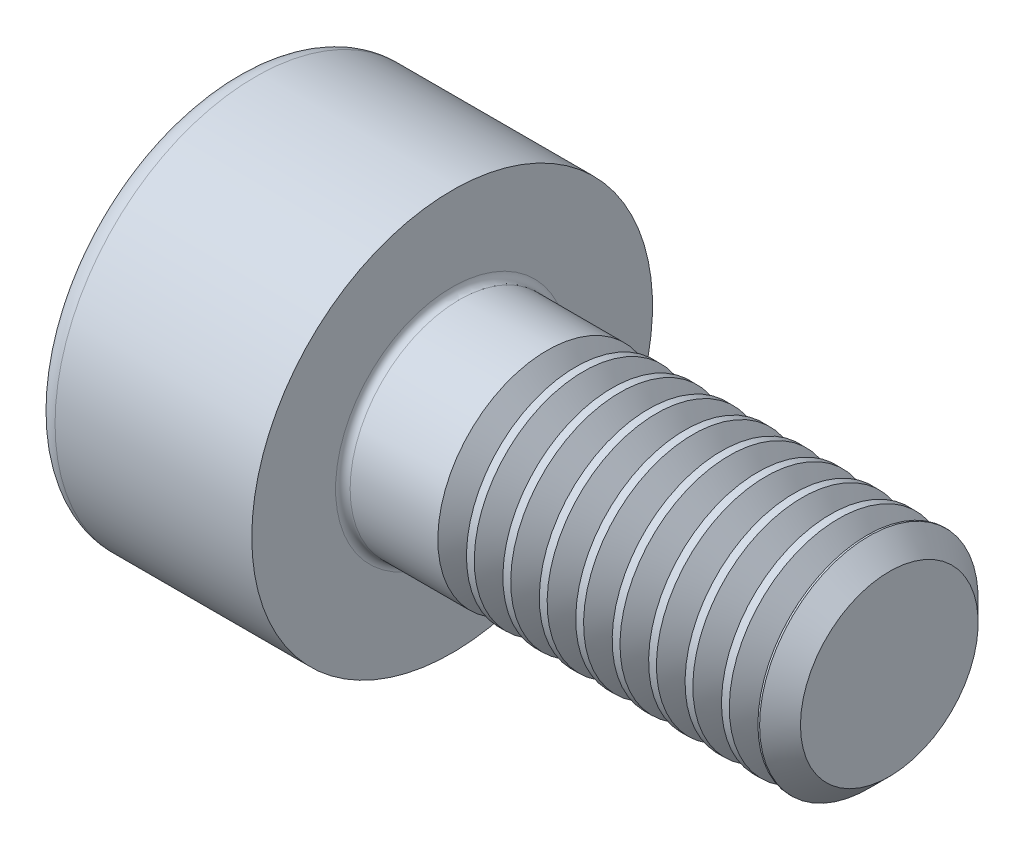
SolidWorks part; units mm, degrees
ref_plane "Plane1" through (0, 0, 0) normal (0, 0, 1) x (1, 0, 0)
ref_plane "Plane2" through (0, 0, 0) normal (0, 1, 0) x (1, 0, 0)
ref_plane "Plane3" through (0, 0, 0) normal (1, 0, 0) x (0, 0, -1)
sketch "BodySke" plane through (0, 0, 0) normal (0, 0, 1) x (1, 0, 0)
  line L0 (0, 0) -> (0, 2.75)
  line L1 (0, 2.75) -> (3, 2.75)
  line L2 (3, 2.75) -> (3, 1.5)
  line L3 (3, 1.5) -> (8.7195, 1.5)
  line L4 (9, 1.2195) -> (9, 0)
  line L5 (9, 0) -> (0, 0)
  line L6 (-31.75, 0) -> (127, 0) construction
  line L8 (9, 1.2195) -> (8.7195, 1.5)
  line L10 (9, -1.2195) -> (8.7195, -1.5) construction
  line L11 (3.5, 9.525) -> (3.5, 3.175) construction
  line L12 (3, 9.525) -> (3, 3.175) construction
  line L13 (-51, 9.525) -> (-51, 3.175) construction
  dimension "Diameter" = 3
  dimension "Head_ht" = 3
  dimension "Length" = 6
  dimension "Body_ch_ang" = 45
  dimension "Head_dia" = 5.5
  dimension "Minor_dia" = 2.439
  dimension "Advance" = 0.5
  dimension "Thread_nom" = 6
  dimension "Thread_length" = 60
revolve "Base-Revolve" add sketch "BodySke"
cosmetic thread "ThreadCosmetic" [suppressed]
fillet "Fillet1" radius 0.1 1 edges at (3, 0, 1.5)
fillet "Fillet2" radius 0.3 1 edges at (0, 0, 2.75)
sketch "Sketch2" plane through (0, 0, 0) normal (0, 0, 1) x (1, 0, 0)
  line L0 (0, 1.26) -> (1.3, 1.26)
  line L1 (1.3, 1.26) -> (2.0275, 0)
  line L2 (-31.75, 0) -> (127, 0) construction
  line L3 (2.0275, 0) -> (0, 0)
  line L4 (0, 0) -> (0, 1.26)
  line L6 (0, 0) -> (47.625, 0) construction
  dimension "D1" = 1.26
  dimension "D2" = 60
  dimension "Depth" = 1.3
revolve "Hex-PreBroach" cut sketch "Sketch2" angle 360 about L6
sketch "Sketch3" plane through (0, 0, 0) normal (-1, 0, 0) x (0, 0.5, 0.866)
  line L0 (0.7275, 1.26) -> (-0.7275, 1.26)
  line L1 (-0.7275, 1.26) -> (-1.4549, 0)
  line L2 (0.7275, 1.26) -> (1.4549, 0)
  line L3 (0.7275, -1.26) -> (1.4549, 0)
  line L4 (0.7275, -1.26) -> (-0.7275, -1.26)
  line L5 (-0.7275, -1.26) -> (-1.4549, 0)
  dimension "D1" = 1.26
  dimension "D2" = 1.26
  dimension "Hex_size" = 2.52
extrude "Hex" cut sketch "Sketch3" against normal blind 1.3
sketch "ThdSchSke" plane through (0, 0, 0) normal (0, 0, 1) x (1, 0, 0)
  line L0 (4.5, -1.2195) -> (4.3036, -1.5)
  line L1 (4.5, -1.2195) -> (4.6964, -1.5)
  line L2 (4.6964, -1.5) -> (4.6964, -1.875)
  line L3 (-3.175, 0) -> (5.1513, 0) construction
  line L4 (0, 2.45) -> (0, -2.45) construction
  line L5 (4.6964, -1.875) -> (4.3036, -1.875)
  line L6 (4.3036, -1.875) -> (4.3036, -1.5)
  dimension "Thread_minor" = 2.439
  dimension "Diameter" = 3
  dimension "Start" = 4.5
  dimension "SideAngle" = 55
  dimension "VeeAngle" = 70
  dimension "Overcut" = 3.75
revolve "ThreadSchematic" cut sketch "ThdSchSke" angle 360 about L3
pattern_linear "ThdSchPat" count 9 spacing 0.5 along (1, 0, 0) of "ThreadSchematic"
equation "\"D2@Sketch3\" = \"Hex_size@Sketch3\" / 2"
equation "\"D1@Sketch3\" = \"Hex_size@Sketch3\" / 2"
equation "\"D1@Sketch2\" = \"Hex_size@Sketch3\" / 2"
equation "\"Thread_minor@ThreadCosmetic\"  =  \"Minor_dia@BodySke\""
equation "\"Depth@Sketch2\" =  \"Key_eng@Hex\""
equation "\"Thread_length@ThreadCosmetic\" = ((sgn( (\"Length@BodySke\" - \"Advance@BodySke\" * 3.0) - \"Thread_nom@BodySke\" )-1)*( (\"Length@BodySke\" - \"Advance@BodySke\" * 3.0) - \"Thread_nom@BodySke\" ))/-2+ \"Thread_nom@BodySke\""
equation "\"Thread_minor@ThdSchSke\" = \"Minor_dia@BodySke\""
equation "\"Diameter@ThdSchSke\" = \"Diameter@BodySke\""
equation "\"Overcut@ThdSchSke\" = \"Diameter@BodySke\" * 1.25"
equation "\"Start@ThdSchSke\" = \"Head_ht@BodySke\" + \"Length@BodySke\" - \"Thread_length@ThreadCosmetic\"  '---Non-countersunk---"
equation "\"Num_threads@ThdSchPat\" = int( \"Thread_length@ThreadCosmetic\" / \"Advance@BodySke\" + 0.999 )  + 1"
equation "\"Advance@ThdSchPat\" = \"Thread_length@ThreadCosmetic\" /  (\"Num_threads@ThdSchPat\" - 1) 'relax it"
equation "\"Num_threads@ThdSchPat\" = \"Num_threads@ThdSchPat\" - sgn( \"Num_threads@ThdSchPat\" - 1) '---chamfered tips only---"
